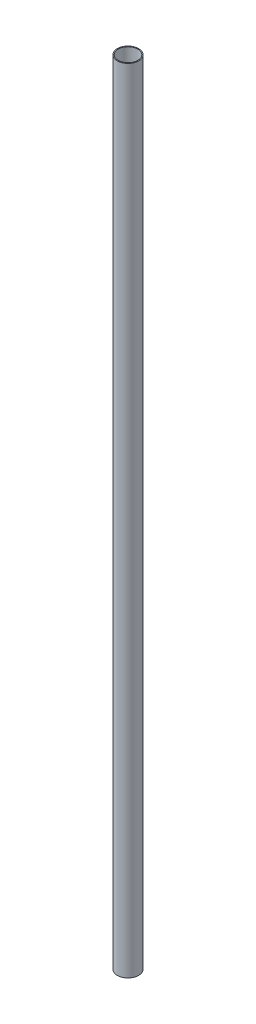
SolidWorks part; units mm, degrees
material "Thornel Mat VMA"
ref_plane "前视基准面" through (0, 0, 0) normal (0, 0, 1) x (1, 0, 0)
ref_plane "上视基准面" through (0, 0, 0) normal (0, 1, 0) x (1, 0, 0)
ref_plane "右视基准面" through (0, 0, 0) normal (1, 0, 0) x (0, 0, -1)
sketch "草图1" plane through (0, 0, 0) normal (0, 1, 0) x (1, 0, 0)
  circle A0 centre (0, 0) radius 5.5
  circle A1 centre (0, 0) radius 6
  dimension "D1" = 12
  dimension "D2" = 0.5
extrude "凸台-拉伸1" add sketch "草图1" along normal blind 445
